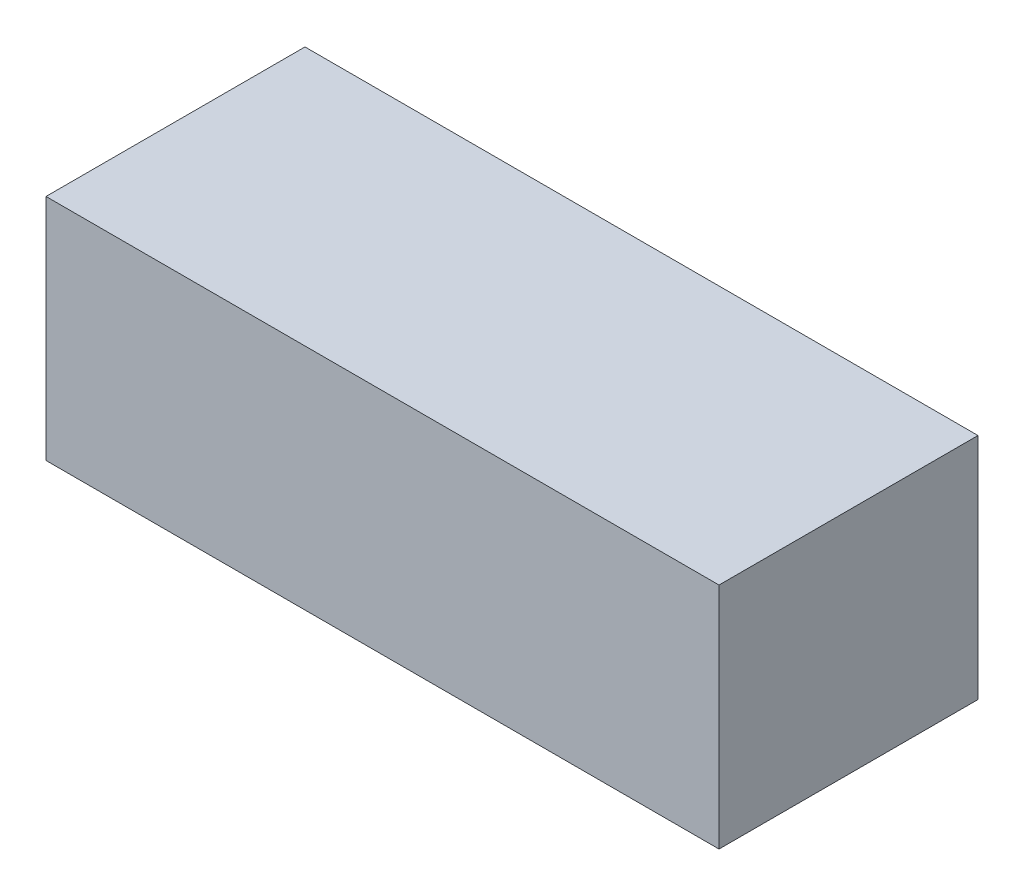
SolidWorks part; units mm, degrees
ref_plane "前视基准面" through (0, 0, 0) normal (0, 0, 1) x (1, 0, 0)
ref_plane "上视基准面" through (0, 0, 0) normal (0, 1, 0) x (1, 0, 0)
ref_plane "右视基准面" through (0, 0, 0) normal (1, 0, 0) x (0, 0, -1)
other "Configuration Table"
sketch "草图1" plane through (0, 0, 0) normal (0, 1, 0) x (1, 0, 0)
  line L1 (0, 0) -> (58.8623, 0)
  line L2 (0, 0) -> (0, 22.65)
  line L3 (0, 22.65) -> (58.8623, 22.65)
  line L4 (58.8623, 0) -> (58.8623, 22.65)
  line L5 (0, 0) -> (58.8623, 22.65) construction
  line L6 (0, 22.65) -> (58.8623, 0) construction
  point P4 (29.4311, 11.325)
extrude "凸台-拉伸1" add sketch "草图1" along normal blind 20
ref_plane "基准面1" through (-854.1377, 0, 0) normal (1, 0, 0) x (0, 0, -1)
